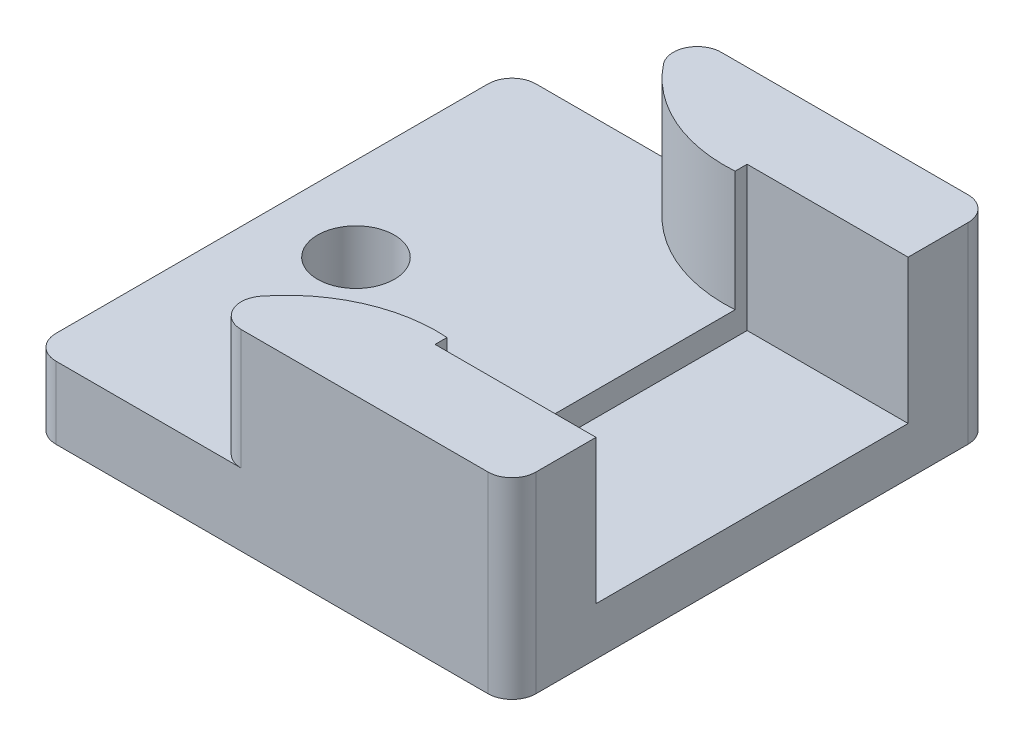
SolidWorks part; units mm, degrees
ref_plane "Alzado" through (0, 0, 0) normal (0, 0, 1) x (1, 0, 0)
ref_plane "Planta" through (0, 0, 0) normal (0, 1, 0) x (1, 0, 0)
ref_plane "Vista lateral" through (0, 0, 0) normal (1, 0, 0) x (0, 0, -1)
sketch "Croquis2" plane through (0, 0, 0) normal (0, 1, 0) x (1, 0, 0)
  line L1 (-10.8434, 8.4739) -> (9.1566, 8.4739)
  line L2 (-10.8434, 8.4739) -> (-10.8434, -11.5261)
  line L3 (-10.8434, -11.5261) -> (9.1566, -11.5261)
  line L4 (9.1566, 8.4739) -> (9.1566, -11.5261)
  dimension "D1" = 20
  dimension "D2" = 20
extrude "Saliente-Extruir1" add sketch "Croquis2" along normal blind 8
sketch "Croquis3" plane through (0, 8, 0) normal (0, 1, 0) x (1, 0, 0)
  line L0 (9.1566, 4.9739) -> (1.1799, 4.9739) construction
  line L1 (9.1566, -11.5261) -> (9.1566, 8.4739) construction
  line L2 (9.1566, -8.0261) -> (5.7192, -8.0261) construction
  line L3 (-10.8434, -11.5261) -> (9.1566, -11.5261) construction
  line L4 (9.1566, 8.4739) -> (-10.8434, 8.4739) construction
  line L6 (9.1566, 4.9739) -> (2.4509, 4.9739)
  line L7 (9.1566, 4.9739) -> (9.1566, -8.0261)
  line L8 (9.1566, -8.0261) -> (2.4509, -8.0261)
  line L9 (2.4509, 4.9739) -> (2.4509, -8.0261)
  dimension "D1" = 3.5
  dimension "D2" = 3.5
extrude "Cortar-Extruir1" cut sketch "Croquis3" against normal blind 6
sketch "Croquis5" plane through (0, 8, 0) normal (0, 1, 0) x (1, 0, 0)
  line L0 (2.4509, 4.9739) -> (-1.2584, 4.9739) construction
  line L1 (2.4509, -8.0261) -> (0, -8.0261) construction
  line L2 (2.4509, 4.9739) -> (2.4509, -8.0261) construction
  line L3 (2.4509, 4.4739) -> (1.59, 4.4739)
  line L4 (2.4509, 4.4739) -> (2.4509, -7.5261)
  line L5 (2.4509, -7.5261) -> (1.59, -7.5261)
  line L7 (-10.8434, 8.4739) -> (9.1566, -11.5261) construction
  line L8 (-0.8434, -1.5261) -> (2.4509, -1.5261) construction
  line L9 (9.1566, 8.4739) -> (-10.8434, 8.4739) construction
  arc A0 (2.4509, 4.4739) -> (-3.8325, 8.4739) centre (2.0204, 10.7329) cw
  arc A1 (2.4509, -7.5261) -> (-3.8325, -11.5261) centre (2.0204, -13.7851) ccw
  line M7 (2.4509, -8.0261) -> (2.4509, 4.9739)
  line M10 (9.1566, 8.4739) -> (-10.8434, 8.4739)
  line M11 (-10.8434, 8.4739) -> (-10.8434, -11.5261)
  line M12 (-10.8434, -11.5261) -> (9.1566, -11.5261)
  dimension "D2" = 12
extrude "Cortar-Extruir2" cut sketch "Croquis5" against normal blind 5 contours A1 A0 M7 M10 M11 M12
sketch "Croquis6" plane through (0, 3, 0) normal (0, 1, 0) x (1, 0, 0)
  line L0 (-7.3434, 8.4739) -> (-7.3434, -11.5261) construction
  line L1 (-3.8325, 8.4739) -> (-10.8434, 8.4739) construction
  line L2 (-10.8434, -11.5261) -> (-3.8325, -11.5261) construction
  line L3 (-10.8434, 8.4739) -> (-10.8434, -11.5261) construction
  circle A0 centre (-7.3434, -1.5261) radius 1.6
  dimension "D2" = 3.2
  dimension "D1" = 3.5
extrude "Cortar-Extruir3" cut sketch "Croquis6" against normal blind 3
fillet "Redondeo1" radius 1 6 edges at (-3.8325, 5.5, -8.4739) (-3.8325, 5.5, 11.5261) (9.1566, 4, -8.4739) (-10.8434, 1.5, -8.4739) (-10.8434, 1.5, 11.5261) (9.1566, 4, 11.5261)
